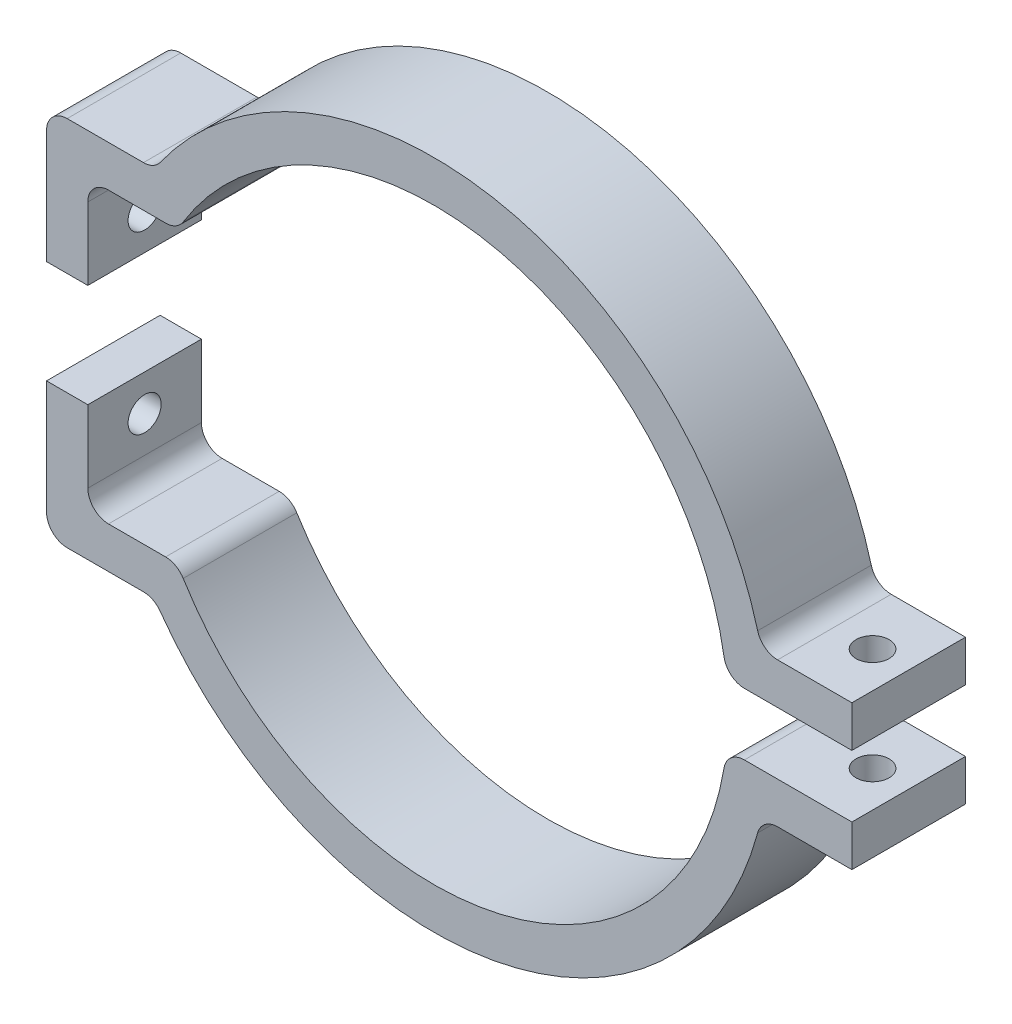
SolidWorks part; units mm, degrees
material "POM 乙缩醛共聚物"
ref_plane "前视基准面" through (0, 0, 0) normal (0, 0, 1) x (1, 0, 0)
ref_plane "上视基准面" through (0, 0, 0) normal (0, 1, 0) x (1, 0, 0)
ref_plane "右视基准面" through (0, 0, 0) normal (1, 0, 0) x (0, 0, -1)
sketch "草图1" plane through (0, 0, 0) normal (0, 0, 1) x (1, 0, 0)
  line L0 (0, 50.0508) -> (0, -44.4451) construction
  line L1 (-58.9099, 0) -> (76.9064, 0) construction
  line L2 (-37.5, 14) -> (-24.8244, 14) construction
  line L11 (-37.5, 18) -> (-22.0964, 18) construction
  line L12 (-37.5, 18) -> (-37.5, 14)
  line L13 (-37.5, -18) -> (-22.0964, -18) construction
  line L14 (-22.0964, 18) -> (-22.0964, -18) construction
  line L15 (-37.5, -14) -> (-24.8244, -14) construction
  line L16 (-37.5, -14) -> (-37.5, -18)
  line L17 (-37.5, 18) -> (-27.0601, 18)
  line L18 (-37.5, -18) -> (-27.0601, -18)
  line L19 (40.5, 3) -> (28.3417, 3)
  line L20 (27.627, 7) -> (40.5, 7) construction
  line L21 (27.627, 7) -> (27.627, -7) construction
  line L22 (27.627, -7) -> (40.5, -7) construction
  line L23 (40.5, 7) -> (40.5, 3)
  line L24 (40.5, -3) -> (28.3417, -3)
  line L25 (31.7372, 7) -> (40.5, 7)
  line L26 (31.7372, -7) -> (40.5, -7)
  line L27 (40.5, -3) -> (40.5, -7)
  line L28 (-37.5, 14) -> (-37.5, -14)
  line L29 (-33.5, -14) -> (-33.5, 14)
  line L30 (-33.5, 14) -> (-24.8244, 14)
  line L31 (-24.8244, -14) -> (-33.5, -14)
  arc A0 (-27.0601, -18) -> (31.7372, -7) centre (0, 0) ccw
  arc A1 (-24.8244, -14) -> (28.3417, -3) centre (0, 0) ccw
  arc A2 (28.3417, 3) -> (-24.8244, 14) centre (0, 0) ccw
  arc A3 (31.7372, 7) -> (-27.0601, 18) centre (0, 0) ccw
  dimension "D1" = 57
  dimension "D2" = 4
  dimension "D3" = 36
  dimension "D4" = 4
  dimension "D5" = 5
  dimension "D6" = 4
  dimension "D7" = 6
  dimension "D8" = 8
  dimension "D9" = 4
extrude "凸台-拉伸1" add sketch "草图1" along normal blind 11
sketch "草图2" plane through (0, 0, 11) normal (0, 0, 1) x (1, 0, 0)
  circle A0 centre (0, 0) radius 28.5
sketch "草图3" plane through (0, 7, 0) normal (0, 1, 0) x (1, 0, 0)
  line L0 (-37.5, -5.5) -> (40.5, -5.5) construction
  line L1 (-37.5, -11) -> (-37.5, 0) construction
  line L2 (40.5, -11) -> (40.5, 0) construction
  circle A0 centre (37, -5.5) radius 1.6
  circle A1 centre (-35, -5.5) radius 1.6 construction
  dimension "D1" = 3.2
  dimension "D2" = 37
  dimension "D3" = 35
extrude "切除-拉伸1" cut sketch "草图3" against normal through all both and the other way through all
sketch "草图5" plane through (-37.5, 0, 0) normal (-1, 0, 0) x (0, 0, 1)
  line L0 (5.5, 18) -> (5.5, -18) construction
  line L1 (11, 18) -> (0, 18) construction
  line L2 (11, -18) -> (0, -18) construction
  line L3 (0, 0) -> (11, 0) construction
  line L4 (11, -28.5) -> (11, 28.5) construction
  line L6 (0, -5) -> (11, -5)
  line L7 (0, -5) -> (0, 5)
  line L8 (0, 5) -> (11, 5)
  line L9 (11, -5) -> (11, 5)
  line L10 (0, -5) -> (11, 5) construction
  line L11 (0, 5) -> (11, -5) construction
  circle A0 centre (5.5, 8.5) radius 1.6
  circle A1 centre (5.5, -8.5) radius 1.6
  point P15 (5.5, 0)
  dimension "D1" = 10
  dimension "D2" = 3.2
  dimension "D3" = 17
extrude "切除-拉伸4" cut sketch "草图5" against normal up to next
fillet "圆角1" radius 2 6 edges at (31.7372, 7, 5.5) (-27.0601, 18, 5.5) (-24.8244, 14, 5.5) (28.3417, 3, 5.5) (-37.5, 18, 5.5) (-33.5, 14, 5.5)
fillet "圆角2" radius 2 6 edges at (28.3417, -3, 5.5) (31.7372, -7, 5.5) (-37.5, -18, 5.5) (-27.0601, -18, 5.5) (-33.5, -14, 5.5) (-24.8244, -14, 5.5)
